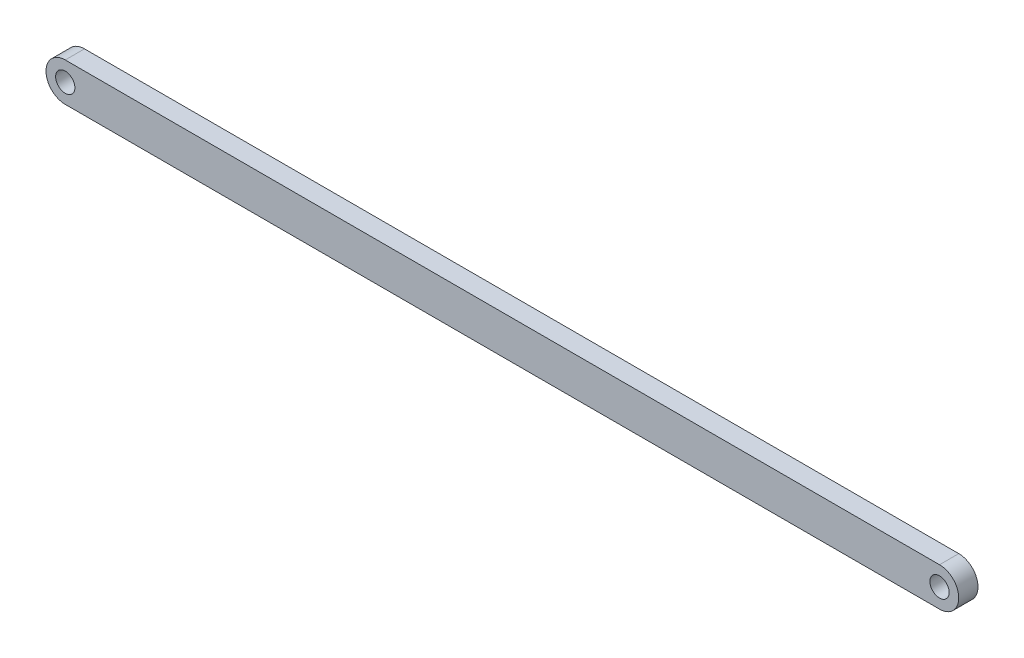
SolidWorks part; units mm, degrees
ref_plane "Plano frontal" through (0, 0, 0) normal (0, 0, 1) x (1, 0, 0)
ref_plane "Plano superior" through (0, 0, 0) normal (0, 1, 0) x (1, 0, 0)
ref_plane "Plano direito" through (0, 0, 0) normal (1, 0, 0) x (0, 0, -1)
sketch "Esboço1" plane through (0, 0, 0) normal (0, 0, 1) x (1, 0, 0)
  line L0 (-113.59, 5) -> (113.59, 5)
  line L1 (-268, 0) -> (268, 0) construction
  line L2 (-113.59, -5) -> (113.59, -5)
  arc A0 (-113.59, 5) -> (-113.59, -5) centre (-113.59, 0) ccw
  arc A1 (113.59, 5) -> (113.59, -5) centre (113.59, 0) cw
  circle A4 centre (113.59, 0) radius 2.5
  circle A5 centre (-113.59, 0) radius 2.5
  point P3 (0, 5)
  dimension "D1" = 227.18
  dimension "D2" = 5
extrude "Ressalto-extrusão1" add sketch "Esboço1" along normal blind 5
